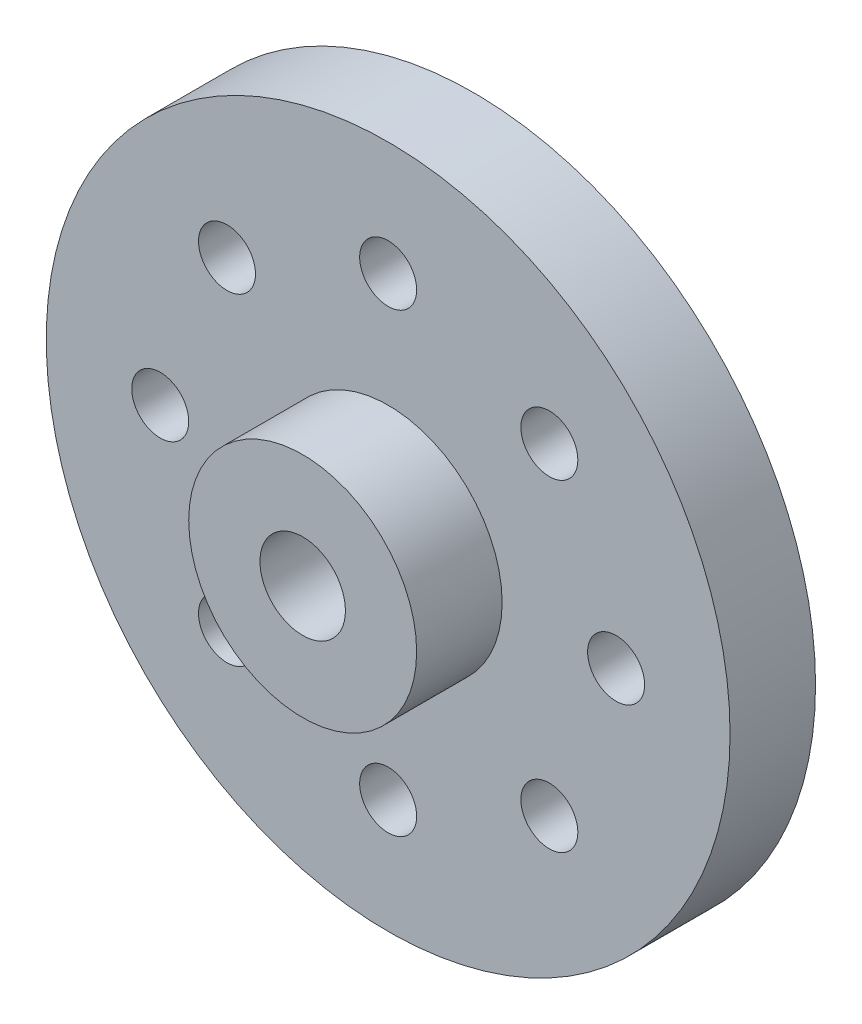
SolidWorks part; units mm, degrees
ref_plane "前视基准面" through (0, 0, 0) normal (0, 0, 1) x (1, 0, 0)
ref_plane "上视基准面" through (0, 0, 0) normal (0, 1, 0) x (1, 0, 0)
ref_plane "右视基准面" through (0, 0, 0) normal (1, 0, 0) x (0, 0, -1)
sketch "草图1" plane through (0, 0, 0) normal (0, 0, 1) x (1, 0, 0)
  circle A0 centre (0, 0) radius 12
  circle A1 centre (0, 0) radius 8 construction
  circle A2 centre (0, 8) radius 1
  circle A3 centre (5.6569, 5.6569) radius 1
  circle A4 centre (8, 0) radius 1
  circle A5 centre (5.6569, -5.6569) radius 1
  circle A6 centre (0, -8) radius 1
  circle A7 centre (-5.6569, -5.6569) radius 1
  circle A8 centre (-8, 0) radius 1
  circle A9 centre (-5.6569, 5.6569) radius 1
  circle A10 centre (0, 0) radius 1.5
  point P23 (0, 0)
  dimension "D1" = 24
  dimension "D2" = 16
  dimension "D3" = 2
  dimension "D5" = 3
  dimension "D4" = 8
extrude "凸台-拉伸1" add sketch "草图1" along normal blind 3
sketch "草图2" plane through (0, 0, 3) normal (0, 0, 1) x (1, 0, 0)
  circle A0 centre (0, 0) radius 1.5
  circle A1 centre (0, 0) radius 4
  dimension "D1" = 8
  dimension "D2" = 3
extrude "凸台-拉伸2" add sketch "草图2" along normal blind 3
